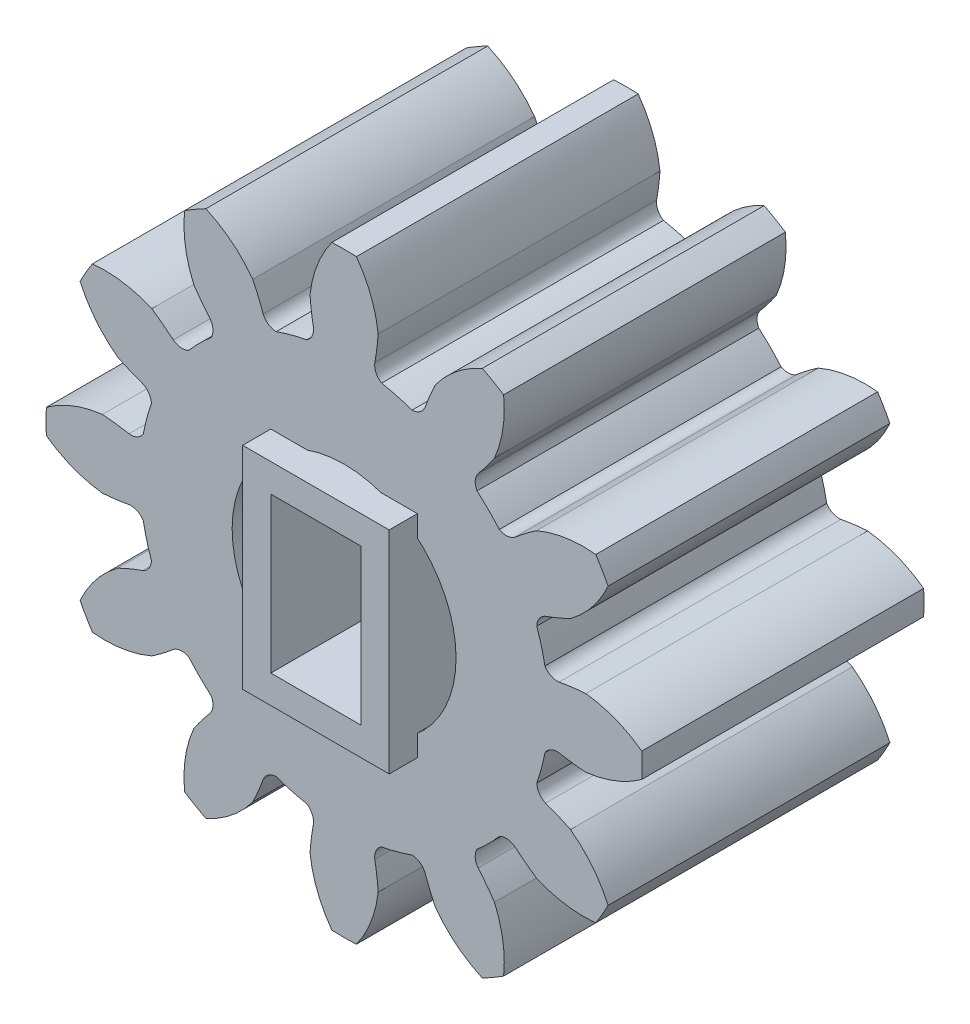
SolidWorks part; units mm, degrees
ref_plane "Front Plane" through (0, 0, 0) normal (0, 0, 1) x (1, 0, 0)
ref_plane "Top Plane" through (0, 0, 0) normal (0, 1, 0) x (1, 0, 0)
ref_plane "Right Plane" through (0, 0, 0) normal (1, 0, 0) x (0, 0, -1)
ref_plane "Plane1" through (0, 0, 20) normal (0, 0, 1) x (1, 0, 0)
ref_plane "Plane2" through (0, 0, 31) normal (0, 0, 1) x (1, 0, 0)
sketch "Sketch1" plane through (0, 0, 20) normal (0, 0, 1) x (1, 0, 0)
  circle A0 centre (0, 20.9252) radius 3.9726
  circle A1 centre (0, 20.9252) radius 7.25
  dimension "D1" = 14.5
sketch "Sketch2" plane through (0, 0, 20) normal (0, 0, 1) x (1, 0, 0)
  arc A0 (-0.4364, 31.4909) -> (0.4364, 31.4909) centre (0, 22.3663) cw
  arc A1 (0.4364, 31.4909) -> (1.2091, 29.5028) centre (-2.9453, 29.0324) cw
  arc A2 (1.2091, 29.5028) -> (1.0888, 28.5542) centre (-7.3823, 30.1104) cw
  arc A3 (1.0888, 28.5542) -> (1.3305, 28.0521) centre (1.5953, 28.4888) ccw
  circle A4 centre (0, 20.9252) radius 7.25 construction
  arc A5 (-1.0888, 28.5542) -> (-1.3305, 28.0521) centre (-1.5953, 28.4888) cw
  arc A6 (-1.2091, 29.5028) -> (-1.0888, 28.5542) centre (7.3823, 30.1104) ccw
  arc A7 (-0.4364, 31.4909) -> (-1.2091, 29.5028) centre (2.9453, 29.0324) ccw
  arc A8 (-1.3305, 28.0521) -> (1.3305, 28.0521) centre (0, 20.9252) cw
  arc A9 (2.4111, 27.7625) -> (4.7157, 26.432) centre (0, 20.9252) cw
  arc A10 (4.7574, 26.9877) -> (4.7157, 26.432) centre (5.1634, 26.6779) ccw
  arc A11 (5.3359, 27.7491) -> (4.7574, 26.9877) centre (-1.8007, 32.5709) cw
  arc A12 (5.6608, 29.8572) -> (5.3359, 27.7491) centre (1.5028, 29.4189) cw
  arc A13 (4.9049, 30.2936) -> (5.6608, 29.8572) centre (0.7205, 22.1732) cw
  arc A14 (4.9049, 30.2936) -> (3.2417, 28.9582) centre (6.6043, 26.4736) ccw
  arc A15 (3.2417, 28.9582) -> (2.8716, 28.0765) centre (10.9858, 25.1887) ccw
  arc A16 (2.8716, 28.0765) -> (2.4111, 27.7625) centre (2.4002, 28.2732) cw
  arc A17 (5.5068, 25.6409) -> (6.8373, 23.3364) centre (0, 20.9252) cw
  arc A18 (7.1513, 23.7968) -> (6.8373, 23.3364) centre (7.3479, 23.3255) ccw
  arc A19 (8.0329, 24.1669) -> (7.1513, 23.7968) centre (4.2634, 31.911) cw
  arc A20 (9.3683, 25.8302) -> (8.0329, 24.1669) centre (5.5483, 27.5296) cw
  arc A21 (8.932, 26.586) -> (9.3683, 25.8302) centre (1.248, 21.6458) cw
  arc A22 (8.932, 26.586) -> (6.8239, 26.2611) centre (8.4937, 22.4281) ccw
  arc A23 (6.8239, 26.2611) -> (6.0625, 25.6826) centre (11.6457, 19.1246) ccw
  arc A24 (6.0625, 25.6826) -> (5.5068, 25.6409) centre (5.7526, 26.0886) cw
  arc A25 (7.1269, 22.2558) -> (7.1269, 19.5947) centre (0, 20.9252) cw
  arc A26 (7.629, 19.8365) -> (7.1269, 19.5947) centre (7.5636, 19.3299) ccw
  arc A27 (8.5776, 19.7162) -> (7.629, 19.8365) centre (9.1851, 28.3075) cw
  arc A28 (10.5657, 20.4889) -> (8.5776, 19.7162) centre (8.1072, 23.8706) cw
  arc A29 (10.5657, 21.3616) -> (10.5657, 20.4889) centre (1.4411, 20.9252) cw
  arc A30 (10.5657, 21.3616) -> (8.5776, 22.1343) centre (8.1072, 17.9799) ccw
  arc A31 (8.5776, 22.1343) -> (7.629, 22.014) centre (9.1851, 13.543) ccw
  arc A32 (7.629, 22.014) -> (7.1269, 22.2558) centre (7.5636, 22.5205) cw
  arc A33 (6.8373, 18.5141) -> (5.5068, 16.2095) centre (0, 20.9252) cw
  arc A34 (6.0625, 16.1679) -> (5.5068, 16.2095) centre (5.7526, 15.7619) ccw
  arc A35 (6.8239, 15.5894) -> (6.0625, 16.1679) centre (11.6457, 22.7259) cw
  arc A36 (8.932, 15.2645) -> (6.8239, 15.5894) centre (8.4937, 19.4224) cw
  arc A37 (9.3683, 16.0203) -> (8.932, 15.2645) centre (1.248, 20.2047) cw
  arc A38 (9.3683, 16.0203) -> (8.0329, 17.6835) centre (5.5483, 14.3209) ccw
  arc A39 (8.0329, 17.6835) -> (7.1513, 18.0537) centre (4.2634, 9.9394) ccw
  arc A40 (7.1513, 18.0537) -> (6.8373, 18.5141) centre (7.3479, 18.525) cw
  arc A41 (4.7157, 15.4185) -> (2.4111, 14.0879) centre (0, 20.9252) cw
  arc A42 (2.8716, 13.774) -> (2.4111, 14.0879) centre (2.4002, 13.5773) ccw
  arc A43 (3.2417, 12.8923) -> (2.8716, 13.774) centre (10.9858, 16.6618) cw
  arc A44 (4.9049, 11.5569) -> (3.2417, 12.8923) centre (6.6043, 15.3769) cw
  arc A45 (5.6608, 11.9933) -> (4.9049, 11.5569) centre (0.7205, 19.6772) cw
  arc A46 (5.6608, 11.9933) -> (5.3359, 14.1014) centre (1.5028, 12.4316) ccw
  arc A47 (5.3359, 14.1014) -> (4.7574, 14.8628) centre (-1.8007, 9.2795) ccw
  arc A48 (4.7574, 14.8628) -> (4.7157, 15.4185) centre (5.1634, 15.1726) cw
  arc A49 (1.3305, 13.7984) -> (-1.3305, 13.7984) centre (0, 20.9252) cw
  arc A50 (-1.0888, 13.2963) -> (-1.3305, 13.7984) centre (-1.5953, 13.3616) ccw
  arc A51 (-1.2091, 12.3476) -> (-1.0888, 13.2963) centre (7.3823, 11.7401) cw
  arc A52 (-0.4364, 10.3595) -> (-1.2091, 12.3476) centre (2.9453, 12.8181) cw
  arc A53 (0.4364, 10.3595) -> (-0.4364, 10.3595) centre (0, 19.4842) cw
  arc A54 (0.4364, 10.3595) -> (1.2091, 12.3476) centre (-2.9453, 12.8181) ccw
  arc A55 (1.2091, 12.3476) -> (1.0888, 13.2963) centre (-7.3823, 11.7401) ccw
  arc A56 (1.0888, 13.2963) -> (1.3305, 13.7984) centre (1.5953, 13.3616) cw
  arc A57 (-2.4111, 14.0879) -> (-4.7157, 15.4185) centre (0, 20.9252) cw
  arc A58 (-4.7574, 14.8628) -> (-4.7157, 15.4185) centre (-5.1634, 15.1726) ccw
  arc A59 (-5.3359, 14.1014) -> (-4.7574, 14.8628) centre (1.8007, 9.2795) cw
  arc A60 (-5.6608, 11.9933) -> (-5.3359, 14.1014) centre (-1.5028, 12.4316) cw
  arc A61 (-4.9049, 11.5569) -> (-5.6608, 11.9933) centre (-0.7205, 19.6772) cw
  arc A62 (-4.9049, 11.5569) -> (-3.2417, 12.8923) centre (-6.6043, 15.3769) ccw
  arc A63 (-3.2417, 12.8923) -> (-2.8716, 13.774) centre (-10.9858, 16.6618) ccw
  arc A64 (-2.8716, 13.774) -> (-2.4111, 14.0879) centre (-2.4002, 13.5773) cw
  arc A65 (-5.5068, 16.2095) -> (-6.8373, 18.5141) centre (0, 20.9252) cw
  arc A66 (-7.1513, 18.0537) -> (-6.8373, 18.5141) centre (-7.3479, 18.525) ccw
  arc A67 (-8.0329, 17.6835) -> (-7.1513, 18.0537) centre (-4.2634, 9.9394) cw
  arc A68 (-9.3683, 16.0203) -> (-8.0329, 17.6835) centre (-5.5483, 14.3209) cw
  arc A69 (-8.932, 15.2645) -> (-9.3683, 16.0203) centre (-1.248, 20.2047) cw
  arc A70 (-8.932, 15.2645) -> (-6.8239, 15.5894) centre (-8.4937, 19.4224) ccw
  arc A71 (-6.8239, 15.5894) -> (-6.0625, 16.1679) centre (-11.6457, 22.7259) ccw
  arc A72 (-6.0625, 16.1679) -> (-5.5068, 16.2095) centre (-5.7526, 15.7619) cw
  arc A73 (-7.1269, 19.5947) -> (-7.1269, 22.2558) centre (0, 20.9252) cw
  arc A74 (-7.629, 22.014) -> (-7.1269, 22.2558) centre (-7.5636, 22.5205) ccw
  arc A75 (-8.5776, 22.1343) -> (-7.629, 22.014) centre (-9.1851, 13.543) cw
  arc A76 (-10.5657, 21.3616) -> (-8.5776, 22.1343) centre (-8.1072, 17.9799) cw
  arc A77 (-10.5657, 20.4889) -> (-10.5657, 21.3616) centre (-1.4411, 20.9252) cw
  arc A78 (-10.5657, 20.4889) -> (-8.5776, 19.7162) centre (-8.1072, 23.8706) ccw
  arc A79 (-8.5776, 19.7162) -> (-7.629, 19.8365) centre (-9.1851, 28.3075) ccw
  arc A80 (-7.629, 19.8365) -> (-7.1269, 19.5947) centre (-7.5636, 19.3299) cw
  arc A81 (-6.8373, 23.3364) -> (-5.5068, 25.6409) centre (0, 20.9252) cw
  arc A82 (-6.0625, 25.6826) -> (-5.5068, 25.6409) centre (-5.7526, 26.0886) ccw
  arc A83 (-6.8239, 26.2611) -> (-6.0625, 25.6826) centre (-11.6457, 19.1246) cw
  arc A84 (-8.932, 26.586) -> (-6.8239, 26.2611) centre (-8.4937, 22.4281) cw
  arc A85 (-9.3683, 25.8302) -> (-8.932, 26.586) centre (-1.248, 21.6458) cw
  arc A86 (-9.3683, 25.8302) -> (-8.0329, 24.1669) centre (-5.5483, 27.5296) ccw
  arc A87 (-8.0329, 24.1669) -> (-7.1513, 23.7968) centre (-4.2634, 31.911) ccw
  arc A88 (-7.1513, 23.7968) -> (-6.8373, 23.3364) centre (-7.3479, 23.3255) cw
  arc A89 (-4.7157, 26.432) -> (-2.4111, 27.7625) centre (0, 20.9252) cw
  arc A90 (-2.8716, 28.0765) -> (-2.4111, 27.7625) centre (-2.4002, 28.2732) ccw
  arc A91 (-3.2417, 28.9582) -> (-2.8716, 28.0765) centre (-10.9858, 25.1887) cw
  arc A92 (-4.9049, 30.2936) -> (-3.2417, 28.9582) centre (-6.6043, 26.4736) cw
  arc A93 (-5.6608, 29.8572) -> (-4.9049, 30.2936) centre (-0.7205, 22.1732) cw
  arc A94 (-5.6608, 29.8572) -> (-5.3359, 27.7491) centre (-1.5028, 29.4189) ccw
  arc A95 (-5.3359, 27.7491) -> (-4.7574, 26.9877) centre (1.8007, 32.5709) ccw
  arc A96 (-4.7574, 26.9877) -> (-4.7157, 26.432) centre (-5.1634, 26.6779) cw
  point P192 (0, 20.9252)
  dimension "D1" = 12
extrude "Boss-Extrude1" add sketch "Sketch2" along normal blind 10
extrude "Boss-Extrude2" add sketch "Sketch1" along normal blind 10
sketch "Sketch3" plane through (0, 0, 31) normal (0, 0, 1) x (1, 0, 0)
  line L0 (-3.9726, 20.9252) -> (15.3734, 20.9252) construction
  line L1 (0, 24.8978) -> (0, 8.7425) construction
  line L3 (-1.6, 23.6752) -> (1.6, 23.6752)
  line L4 (-1.6, 23.6752) -> (-1.6, 18.1752)
  line L5 (-1.6, 18.1752) -> (1.6, 18.1752)
  line L6 (1.6, 23.6752) -> (1.6, 18.1752)
  circle A0 centre (0, 20.9252) radius 3.9726 construction
  dimension "D1" = 3.2
  dimension "D2" = 5.5
  dimension "D3" = 1.6
  dimension "D4" = 2.75
extrude "Boss-Extrude4" add sketch "Sketch3" against normal blind 10 separate body
shell "Shell2" thickness 1
